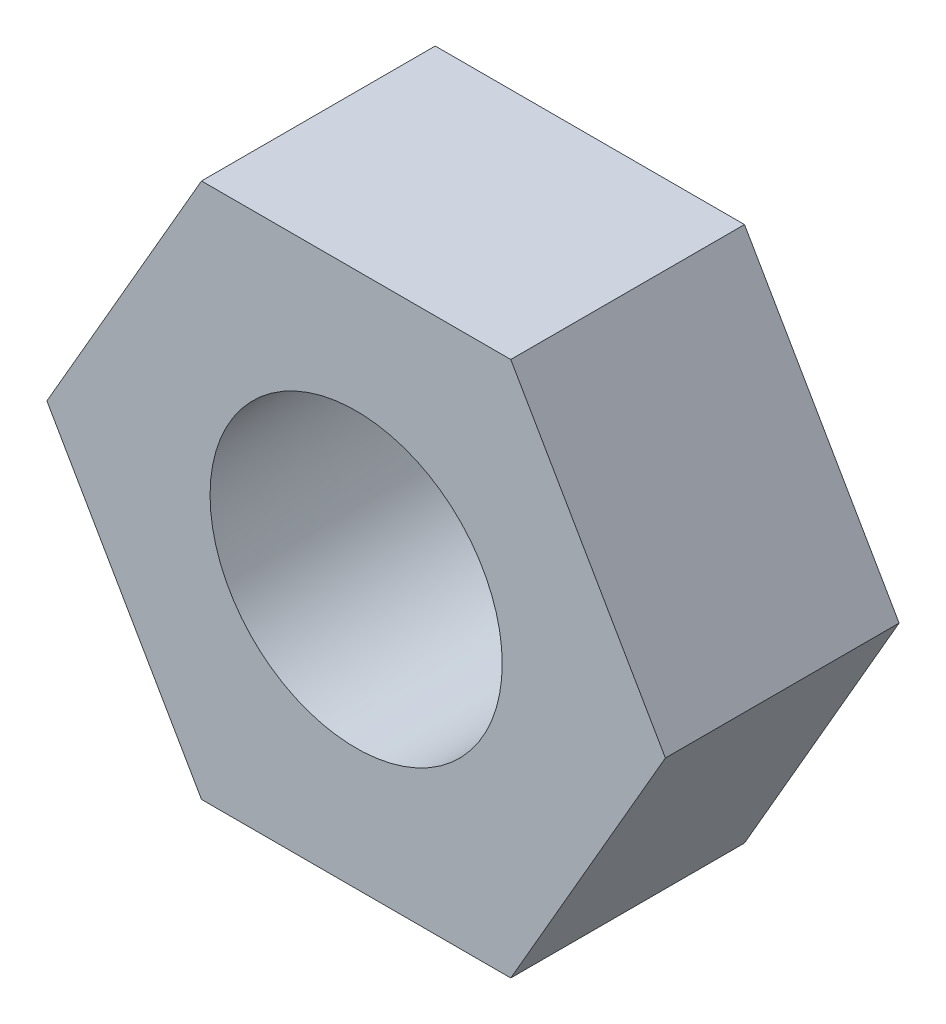
SolidWorks part; units mm, degrees
ref_plane "前视基准面" through (0, 0, 0) normal (0, 0, 1) x (1, 0, 0)
ref_plane "上视基准面" through (0, 0, 0) normal (0, 1, 0) x (1, 0, 0)
ref_plane "右视基准面" through (0, 0, 0) normal (1, 0, 0) x (0, 0, -1)
other "Configuration Table"
sketch "草图1" plane through (0, 0, 0) normal (0, 0, 1) x (1, 0, 0)
  line L1 (-1.5877, 2.75) -> (-3.1754, 0)
  line L2 (-3.1754, 0) -> (-1.5877, -2.75)
  line L3 (-1.5877, -2.75) -> (1.5877, -2.75)
  line L4 (1.5877, -2.75) -> (3.1754, 0)
  line L5 (3.1754, 0) -> (1.5877, 2.75)
  line L6 (1.5877, 2.75) -> (-1.5877, 2.75)
  circle A0 centre (0, 0) radius 1.5
  circle A1 centre (0, 0) radius 2.75 construction
  dimension "D1" = 3
extrude "凸台-拉伸1" add sketch "草图1" along normal blind 2.4
